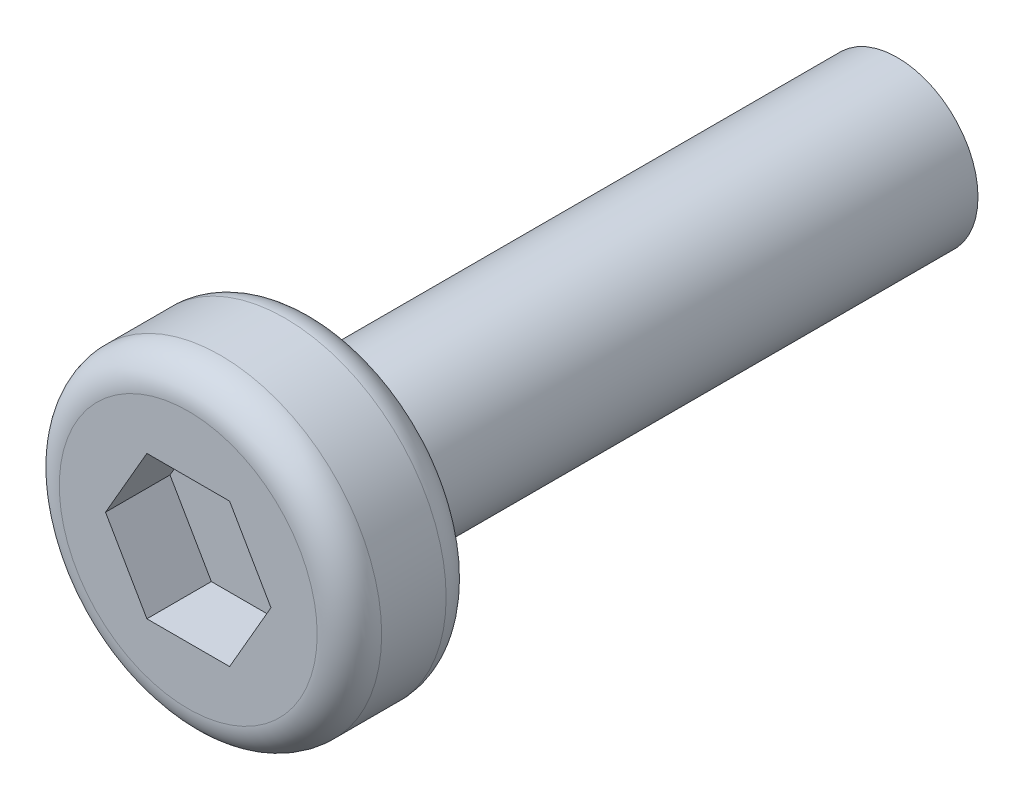
SolidWorks part; units mm, degrees
ref_plane "Front Plane" through (0, 0, 0) normal (0, 0, 1) x (1, 0, 0)
ref_plane "Top Plane" through (0, 0, 0) normal (0, 1, 0) x (1, 0, 0)
ref_plane "Right Plane" through (0, 0, 0) normal (1, 0, 0) x (0, 0, -1)
sketch "Sketch1" plane through (0, 0, 0) normal (0, 0, 1) x (1, 0, 0)
  circle A0 centre (0, 0) radius 1.25
extrude "Boss-Extrude1" add sketch "Sketch1" against normal blind 9
sketch "Sketch2" plane through (0, 0, 0) normal (0, 0, 1) x (1, 0, 0)
  circle A0 centre (0, 0) radius 2.5
extrude "Boss-Extrude2" add sketch "Sketch2" along normal blind 2
sketch "Sketch3" plane through (0, 0, 2) normal (0, 0, 1) x (1, 0, 0)
  line L1 (1.283, 0) -> (0.6415, 1.1111)
  line L2 (0.6415, 1.1111) -> (-0.6415, 1.1111)
  line L3 (-0.6415, 1.1111) -> (-1.283, 0)
  line L4 (-1.283, 0) -> (-0.6415, -1.1111)
  line L5 (-0.6415, -1.1111) -> (0.6415, -1.1111)
  line L6 (0.6415, -1.1111) -> (1.283, 0)
  circle A0 centre (0, 0) radius 1.1111 construction
extrude "Cut-Extrude1" cut sketch "Sketch3" against normal blind 1
fillet "Fillet1" radius 0.5 2 edges at (2.5, 0, 0) (2.5, 0, 2)
